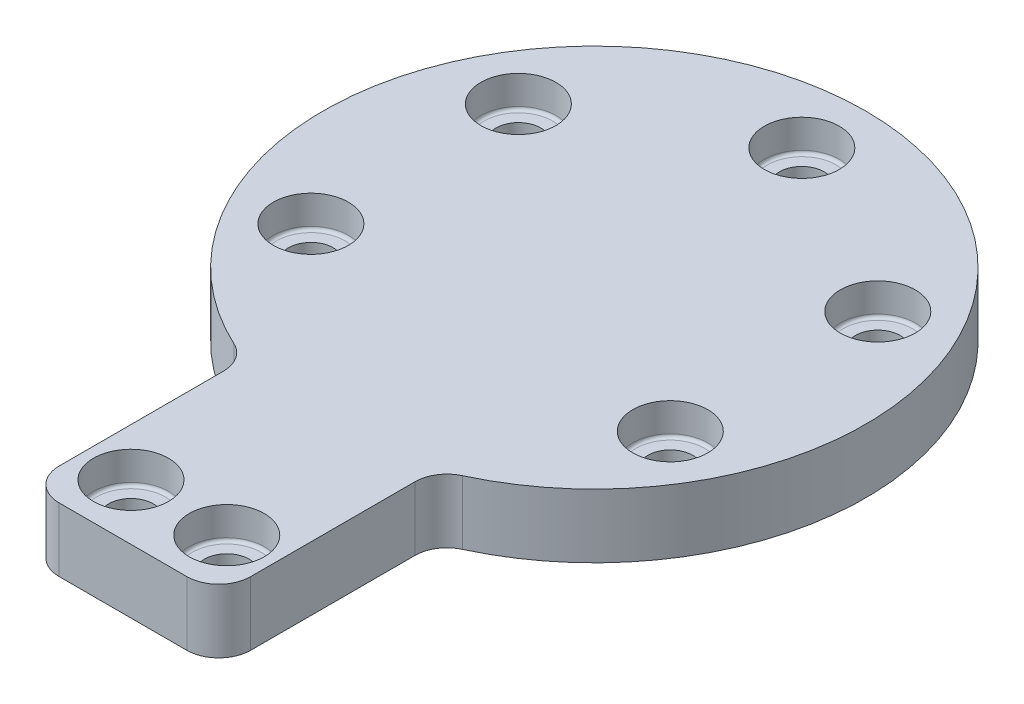
SolidWorks part; units mm, degrees
ref_plane "前视基准面" through (0, 0, 0) normal (0, 0, 1) x (1, 0, 0)
ref_plane "上视基准面" through (0, 0, 0) normal (0, 1, 0) x (1, 0, 0)
ref_plane "右视基准面" through (0, 0, 0) normal (1, 0, 0) x (0, 0, -1)
other "Configuration Table"
sketch "草图1" plane through (0, 0, 0) normal (0, 1, 0) x (1, 0, 0)
  line L0 (0, 0) -> (0, -45.6514) construction
  line L1 (-6, -22.03) -> (-6, -27.53)
  line L2 (-4, -29.53) -> (4, -29.53)
  line L3 (0, -22.03) -> (-11.9402, -22.03) construction
  line L4 (-6, -22.03) -> (-6, -15.906)
  line L5 (6, -22.03) -> (6, -27.53)
  line L6 (6, -22.03) -> (6, -15.906)
  line L7 (-14.7224, -8.5) -> (0, 0) construction
  line L8 (0, 0) -> (0, 17) construction
  line L9 (0, 0) -> (14.7224, -8.5) construction
  line L10 (0, 0) -> (-14.7224, 8.5) construction
  line L11 (0, 0) -> (14.7224, 8.5) construction
  circle A0 centre (0, 0) radius 17 construction
  arc A1 (-6, -27.53) -> (-4, -29.53) centre (-4, -27.53) ccw
  arc A2 (6, -27.53) -> (4, -29.53) centre (4, -27.53) cw
  arc A3 (-6, -15.906) -> (6, -15.906) centre (0, 0) cw
  circle A4 centre (-3, -26.03) radius 1.4
  circle A5 centre (3, -26.03) radius 1.4
  circle A6 centre (0, 0) radius 13 construction
  circle A7 centre (0, 13) radius 1.4
  circle A8 centre (11.2583, -6.5) radius 1.4
  circle A9 centre (-11.2583, -6.5) radius 1.4
  circle A10 centre (-11.2583, 6.5) radius 1.4
  circle A11 centre (11.2583, 6.5) radius 1.4
  point P15 (0, -29.53)
  dimension "D1" = 34
  dimension "D2" = 2
  dimension "D8" = 3.5
  dimension "D11" = 2.8
  dimension "D12" = 2.8
  dimension "D14" = 26
  dimension "D15" = 2.8
  dimension "D18" = 2.8
  dimension "D19" = 2.8
  dimension "D3" = 4
  dimension "D4" = 7.5
  dimension "D5" = 22.03
  dimension "D6" = 3.5
  dimension "D7" = 120
  dimension "D9" = 3
  dimension "D10" = 6
  dimension "D13" = 120
  dimension "D16" = 60
  dimension "D17" = 60
extrude "凸台-拉伸1" add sketch "草图1" along normal blind 4
sketch "草图2" plane through (0, 4, 0) normal (0, 1, 0) x (1, 0, 0)
  circle A0 centre (0, 13) radius 2.35
  circle A1 centre (11.2583, 6.5) radius 2.35
  circle A2 centre (11.2583, -6.5) radius 2.35
  circle A3 centre (-11.2583, -6.5) radius 2.35
  circle A4 centre (-11.2583, 6.5) radius 2.35
  circle A5 centre (-3, -26.03) radius 2.35
  circle A6 centre (3, -26.03) radius 2.35
  dimension "D1" = 4.7
  dimension "D2" = 4.7
extrude "切除-拉伸1" cut sketch "草图2" against normal blind 2
fillet "圆角1" radius 0.2 7 edges at (-3, 2, 28.38) (3, 2, 28.38) (-11.2583, 2, 8.85) (-11.2583, 2, -4.15) (11.2583, 2, 8.85) (11.2583, 2, -4.15) (0, 2, -10.65)
fillet "圆角2" radius 2 2 edges at (6, 2, 15.906) (-6, 2, 15.906)
sketch "草图3" plane through (0, 4, 0) normal (0, 1, 0) x (1, 0, 0)
  line L0 (0, 17) -> (0, -29.53) construction
  line L1 (-4, -29.53) -> (4, -29.53) construction
  arc A0 (7.1579, -15.4196) -> (-7.1579, -15.4196) centre (0, 0) ccw construction
  point P9 (0, -29.53)
